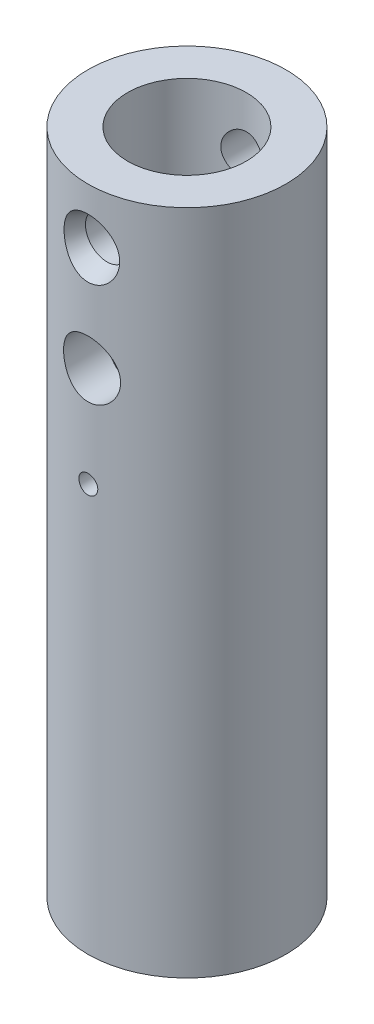
SolidWorks part; units mm, degrees
ref_plane "Front Plane" through (0, 0, 0) normal (0, 0, 1) x (1, 0, 0)
ref_plane "Top Plane" through (0, 0, 0) normal (0, 1, 0) x (1, 0, 0)
ref_plane "Right Plane" through (0, 0, 0) normal (1, 0, 0) x (0, 0, -1)
sketch "Sketch1" plane through (0, 0, 0) normal (0, 1, 0) x (1, 0, 0)
  circle A0 centre (0, 0) radius 7.9375
extrude "Boss-Extrude1" add sketch "Sketch1" along normal blind 53.467
ref_plane "Plane1" through (0, 0, 7.9375) normal (0, 0, 1) x (1, 0, 0)
sketch "Sketch7" plane through (0, 0, 7.9375) normal (0, 0, 1) x (1, 0, 0)
  line L0 (7.9375, 53.467) -> (-7.9375, 53.467) construction
  line L1 (7.9375, 53.467) -> (-7.9375, 53.467)
  point P0 (0, 49.022)
  point P1 (0, 40.64)
  point P2 (0, 32.639)
  point P6 (0, 53.467)
  dimension "D1" = 4.445
  dimension "D2" = 12.827
  dimension "D3" = 20.828
hole_wizard "#29 (0.136) Diameter Hole1" positions "Sketch8" profile "Sketch9" hole size "#29" standard "ANSI Inch" end condition through all
sketch "Sketch8" plane through (0, 0, 7.9375) normal (0, 0, 1) x (1, 0, 0)
  point P0 (0, 49.022)
sketch "Sketch9" plane through (0, 49.022, 7.9375) normal (1, 0, 0) x (0, -1, 0)
  line L0 (0, 0) -> (0, 15.875)
  line L1 (0, 15.875) -> (1.7272, 15.875)
  line L2 (1.7272, 15.875) -> (1.7272, 1.533)
  line L3 (1.7272, 1.533) -> (2.3622, 0)
  line L5 (2.3622, 0) -> (0, 0)
  line L6 (-1.7272, 1.533) -> (-2.3622, 0) construction
  line L11 (0, -6.35) -> (0, 107.95) construction
  dimension "Thru Hole Dia." = 3.4544
  dimension "Thru Hole Depth" = 15.875
  dimension "Near C'Sink Dia." = 4.7244
  dimension "Near C'Sink Angle" = 45
hole_wizard "#15 (0.18) Diameter Hole1" positions "Sketch10" profile "Sketch11" hole size "#15" standard "ANSI Inch" end condition through all
sketch "Sketch10" plane through (0, 0, 7.9375) normal (0, 0, 1) x (1, 0, 0)
  point P0 (0, 40.64)
sketch "Sketch11" plane through (0, 40.64, 7.9375) normal (1, 0, 0) x (0, -1, 0)
  line L0 (0, 0) -> (0, 15.875)
  line L1 (0, 15.875) -> (2.286, 15.875)
  line L2 (2.286, 15.875) -> (2.286, 0)
  line L5 (2.286, 0) -> (0, 0)
  line L11 (0, -6.35) -> (0, 107.95) construction
  dimension "Thru Hole Dia." = 4.572
  dimension "Thru Hole Depth" = 15.875
hole_wizard "#53 (0.0595) Diameter Hole1" positions "Sketch12" profile "Sketch13" hole size "#53" standard "ANSI Inch" end condition through all
sketch "Sketch12" plane through (0, 0, 7.9375) normal (0, 0, 1) x (1, 0, 0)
  point P0 (0, 32.639)
sketch "Sketch13" plane through (0, 32.639, 7.9375) normal (1, 0, 0) x (0, -1, 0)
  line L0 (0, 0) -> (0, 15.875)
  line L1 (0, 15.875) -> (0.7556, 15.875)
  line L2 (0.7556, 15.875) -> (0.7556, 0)
  line L5 (0.7556, 0) -> (0, 0)
  line L11 (0, -6.35) -> (0, 107.95) construction
  dimension "Thru Hole Dia." = 1.5113
  dimension "Thru Hole Depth" = 15.875
hole_wizard "3/8 (0.375) Diameter Hole1" positions "Sketch15" profile "Sketch16" hole size "3/8" standard "ANSI Inch"
sketch "Sketch15" plane through (0, 53.467, 0) normal (0, 1, 0) x (1, 0, 0)
  point P0 (0, 0)
sketch "Sketch16" plane through (0, 53.467, 0) normal (1, 0, 0) x (0, 0, 1)
  line L0 (0, 0) -> (0, 53.6616)
  line L1 (0, 53.6616) -> (4.7625, 50.8)
  line L2 (4.7625, 50.8) -> (4.7625, 0)
  line L5 (4.7625, 0) -> (0, 0)
  line L10 (0, 53.6616) -> (-4.7625, 50.8) construction
  line L11 (0, -6.35) -> (0, 107.95) construction
  dimension "Hole Dia." = 9.525
  dimension "Hole Depth" = 50.8
  dimension "Drill Angle" = 118
hole_wizard "#39 (0.0995) Diameter Hole1" positions "Sketch18" profile "Sketch19" hole size "#39" standard "ANSI Inch" end condition through all
sketch "Sketch18" plane through (0, 0, 0) normal (0, -1, 0) x (-1, 0, 0)
  point P0 (0, 0)
sketch "Sketch19" plane through (0, 0, 0) normal (1, 0, 0) x (0, 0, -1)
  line L0 (0, 0) -> (0, 53.467)
  line L1 (0, 53.467) -> (1.27, 53.467)
  line L2 (1.27, 53.467) -> (1.27, 0)
  line L5 (1.27, 0) -> (0, 0)
  line L11 (0, -6.35) -> (0, 107.95) construction
  dimension "Thru Hole Dia." = 2.54
  dimension "Thru Hole Depth" = 53.467
